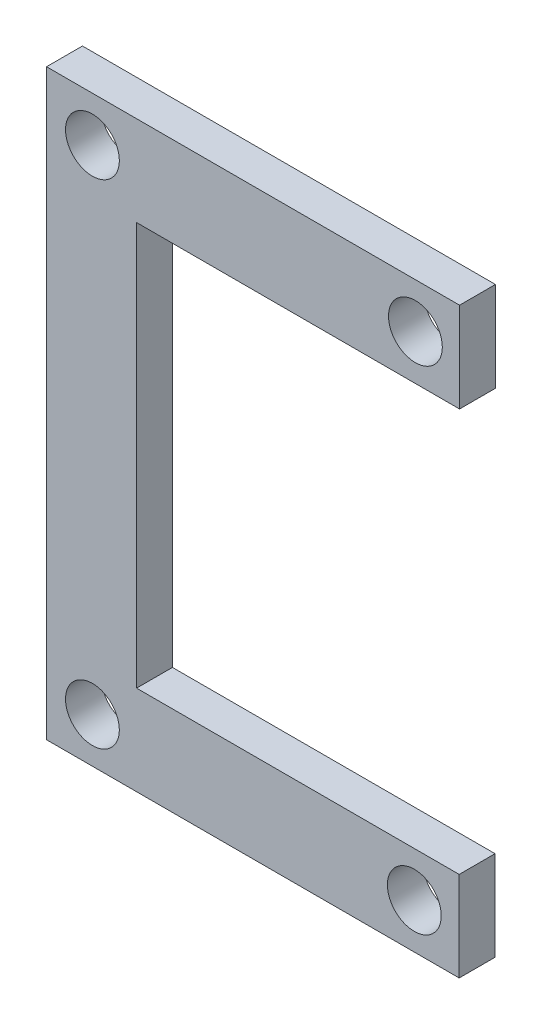
SolidWorks part; units mm, degrees
ref_plane "Front Plane" through (0, 0, 0) normal (0, 0, 1) x (1, 0, 0)
ref_plane "Top Plane" through (0, 0, 0) normal (0, 1, 0) x (1, 0, 0)
ref_plane "Right Plane" through (0, 0, 0) normal (1, 0, 0) x (0, 0, -1)
sketch "Sketch1" plane through (0, 0, 0) normal (0, 0, 1) x (1, 0, 0)
  line L12 (-65.9815, -14.5345) -> (-88.9981, -14.5345)
  line L13 (-88.9981, -14.5345) -> (-88.9981, -47.0171)
  line L14 (-88.9981, -47.0171) -> (-66.0032, -47.0171)
  line L15 (-66.0032, -47.0171) -> (-66.0032, -42.0171)
  line L16 (-66.0032, -42.0171) -> (-83.9815, -42.0171)
  line L17 (-83.9815, -42.0171) -> (-83.9815, -19.546)
  line L18 (-83.9815, -19.546) -> (-65.9815, -19.546)
  line L19 (-65.9815, -19.546) -> (-65.9815, -14.5345)
  circle A0 centre (-68.4428, -17.0402) radius 1.5
  circle A1 centre (-86.4415, -17.0402) radius 1.5
  circle A2 centre (-86.4415, -44.5171) radius 1.5
  circle A3 centre (-68.5032, -44.5171) radius 1.5
extrude "Boss-Extrude2" add sketch "Sketch1" along normal blind 2 contours L19 L12 L13 L14 L15 L16 L17 L18 | A0 | A1 | A2 | A3
